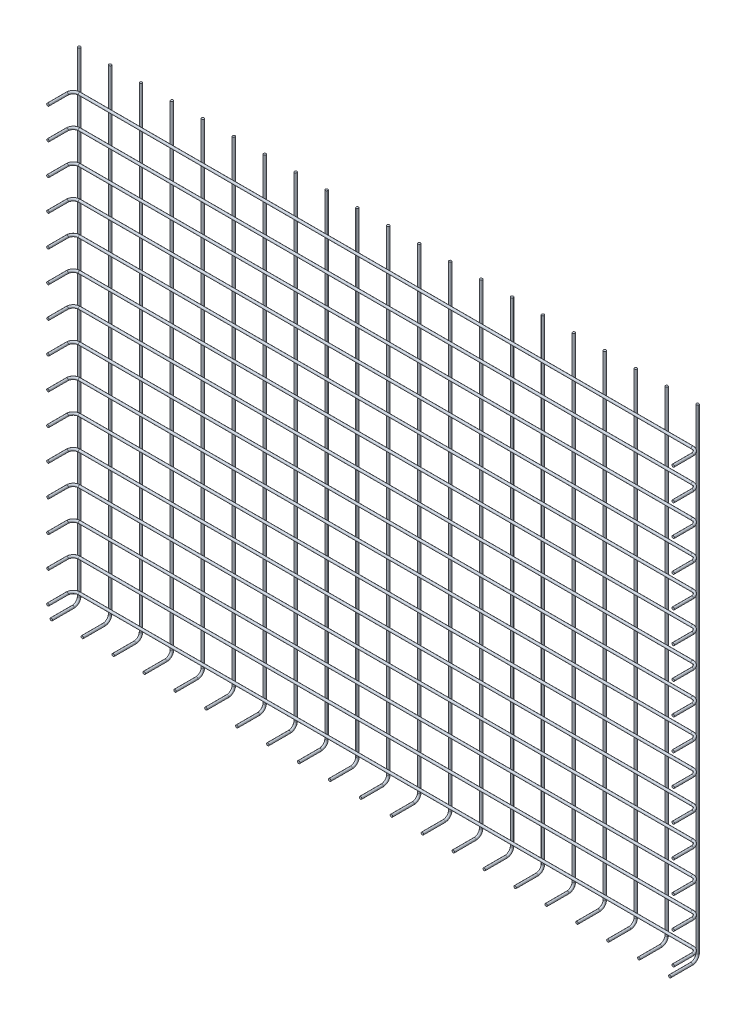
SolidWorks part; units mm, degrees
material "AISI 1020"
ref_plane "Спереди" through (0, 0, 0) normal (0, 0, 1) x (1, 0, 0)
ref_plane "Сверху" through (0, 0, 0) normal (0, 1, 0) x (1, 0, 0)
ref_plane "Справа" through (0, 0, 0) normal (1, 0, 0) x (0, 0, -1)
sketch "Эскиз1" plane through (0, 0, 47) normal (0, 0, 1) x (1, 0, 0)
  line L1 (507.5, 0) -> (-507.5, 0) construction
  circle A0 centre (0, 2) radius 2
  point P1 (0, 0)
  point P6 (0, 0)
  dimension "D1" = 4
sketch "Эскиз2" plane through (0, 0, 0) normal (1, 0, 0) x (0, 0, -1)
  line L0 (-47, 2) -> (-12, 2)
  line L1 (-2, 12) -> (-2, 781.0566)
  line L6 (-0.75, 761.0566) -> (3, 761.0566) construction
  arc A0 (-12, 2) -> (-2, 12) centre (-12, 12) ccw
  point P2 (0, 0)
  point P4 (-2, 188.6587)
  point P5 (-2, 793.5605)
  point P10 (1.125, 761.0566)
  dimension "D3" = 10
  dimension "D1" = 2
  dimension "D2" = 20
sweep "По траектории1" add profiles "Эскиз1" path "Эскиз2"
pattern_linear "Линейный массив2" count 11 spacing 50 along (1, 0, 0) of bodies 103
mirror "Зеркальное отражение1" about plane through (0, 0, 0) normal (1, 0, 0) of bodies 113 112 111 110 109 108 107 105 104 106
ref_plane "Плоскость1" through (0, 20, 0) normal (0, 1, 0) x (1, 0, 0)
sketch "Эскиз3" plane through (0, 20, 0) normal (0, 1, 0) x (1, 0, 0)
  line L0 (-505.5, -47) -> (-505.5, -16)
  line L1 (-495.5, -6) -> (495.5, -6)
  line L2 (505.5, -16) -> (505.5, -47)
  line L3 (-507.5, -1671) -> (-507.5, 108.1025) construction
  line L4 (507.5, -1671) -> (507.5, 108.1025) construction
  line L5 (554.5, -47) -> (510.5, -47) construction
  circle A0 centre (0, -2) radius 2 construction
  arc A1 (-505.5, -16) -> (-495.5, -6) centre (-495.5, -16) cw
  arc A2 (495.5, -6) -> (505.5, -16) centre (495.5, -16) cw
  point P10 (0, 0)
  dimension "D1" = 4
  dimension "D4" = 10
  dimension "D2" = 2
  dimension "D3" = 2
sketch "Эскиз4" plane through (0, 0, 47) normal (0, 0, 1) x (1, 0, 0)
  circle A0 centre (-505.5, 20) radius 2
  dimension "D1" = 4
sweep "По траектории2" add profiles "Эскиз4" path "Эскиз3"
pattern_linear "Линейный массив3" count 15 spacing 50 along (0, 1, 0) of bodies 124
